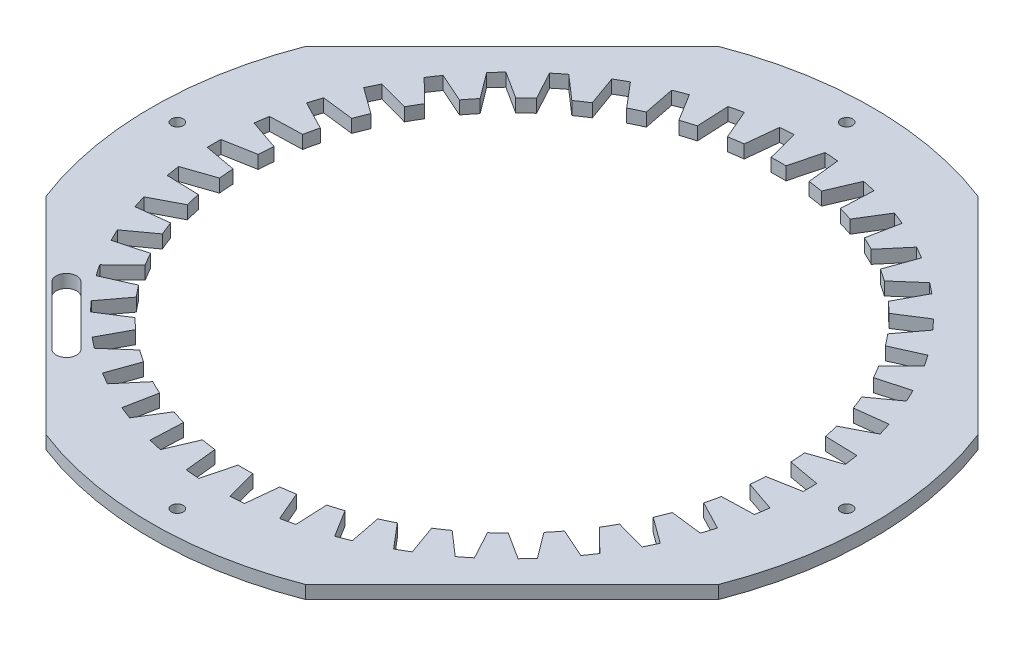
SolidWorks part; units mm, degrees
ref_plane "Front Plane" through (0, 0, 0) normal (0, 0, 1) x (1, 0, 0)
ref_plane "Top Plane" through (0, 0, 0) normal (0, 1, 0) x (1, 0, 0)
ref_plane "Right Plane" through (0, 0, 0) normal (1, 0, 0) x (0, 0, -1)
sketch "Sketch1" plane through (0, 0, 0) normal (0, 1, 0) x (1, 0, 0)
  line L0 (-81.25, 0) -> (81.25, 0) construction
  line L2 (0, 81.25) -> (0, -81.25) construction
  circle A0 centre (0, 0) radius 87.5
  circle A1 centre (0, 0) radius 72.3582 construction
  circle A3 centre (0, 0) radius 64.7332
  circle A4 centre (-81.25, 0) radius 1.425
  circle A5 centre (0, 81.25) radius 1.425
  circle A6 centre (81.25, 0) radius 1.425
  circle A7 centre (0, -81.25) radius 1.425
  dimension "D1" = 2.85
  dimension "D2" = 175
  dimension "D3" = 144.7164
  dimension "D5" = 7.625
  dimension "D4" = 162.5
extrude "Boss-Extrude1" add sketch "Sketch1" along normal blind 3.175
sketch "Sketch2" plane through (0, 3.175, 0) normal (0, 1, 0) x (1, 0, 0)
  line L2 (64.6612, 3.0514) -> (72.3392, 1.6584)
  line L3 (0, 0) -> (72.3582, 0) construction
  line L4 (64.6612, -3.0514) -> (72.3392, -1.6584)
  circle A0 centre (0, 0) radius 72.3582 construction
  arc A1 (64.6612, 3.0514) -> (64.6612, -3.0514) centre (0, 0) cw
  circle A2 centre (0, 0) radius 64.7332 construction
  arc A3 (72.3392, 1.6584) -> (72.3392, -1.6584) centre (0, 0) cw
  point P11 (72.3582, 0)
  point P14 (64.7332, 0)
  dimension "D1" = 144.7164
  dimension "D2" = 3.3168
  dimension "D3" = 6.1029
extrude "Cut-Extrude1" cut sketch "Sketch2" against normal through all
pattern_circular "CirPattern1" count 42 over 360 about axis through (0, 0, 0) along (0, 1, 0) of "Cut-Extrude1"
sketch "Sketch3" plane through (0, 3.175, 0) normal (0, 1, 0) x (1, 0, 0)
  line L1 (113.1371, 0) -> (0, -113.1371)
  line L2 (113.1371, 0) -> (0, 113.1371)
  line L3 (0, 113.1371) -> (-113.1371, 0)
  line L4 (0, -113.1371) -> (-113.1371, 0)
  line L5 (113.1371, 0) -> (-113.1371, 0) construction
  line L6 (0, 113.1371) -> (0, -113.1371) construction
  circle A0 centre (0, 0) radius 113.1371
  circle A2 centre (0, 0) radius 87.5 construction
  point P0 (0, 0)
  point P9 (-56.5685, 56.5685)
  dimension "D1" = 80
extrude "Cut-Extrude2" cut sketch "Sketch3" against normal through all contours L3 A0 | L2 A0 | L1 A0 | L4 A0
sketch "Sketch4" plane through (0, 3.175, 0) normal (0, 1, 0) x (1, 0, 0)
  line L0 (-61.1647, -47.0226) -> (-47.0226, -61.1647) construction
  line L1 (-59.397, -45.2548) -> (-45.2548, -59.397)
  line L2 (-62.9325, -48.7904) -> (-48.7904, -62.9325)
  line L3 (-54.0937, -54.0937) -> (0, 0) construction
  line L4 (-31.5061, -81.631) -> (-81.631, -31.5061) construction
  arc A0 (-59.397, -45.2548) -> (-62.9325, -48.7904) centre (-61.1647, -47.0226) ccw
  arc A1 (-48.7904, -62.9325) -> (-45.2548, -59.397) centre (-47.0226, -61.1647) ccw
  point P2 (-54.0937, -54.0937)
  point P10 (-55.7618, -51.9222)
  dimension "D1" = 20
  dimension "D2" = 5
  dimension "D3" = 3.5
extrude "Cut-Extrude3" cut sketch "Sketch4" against normal through all
